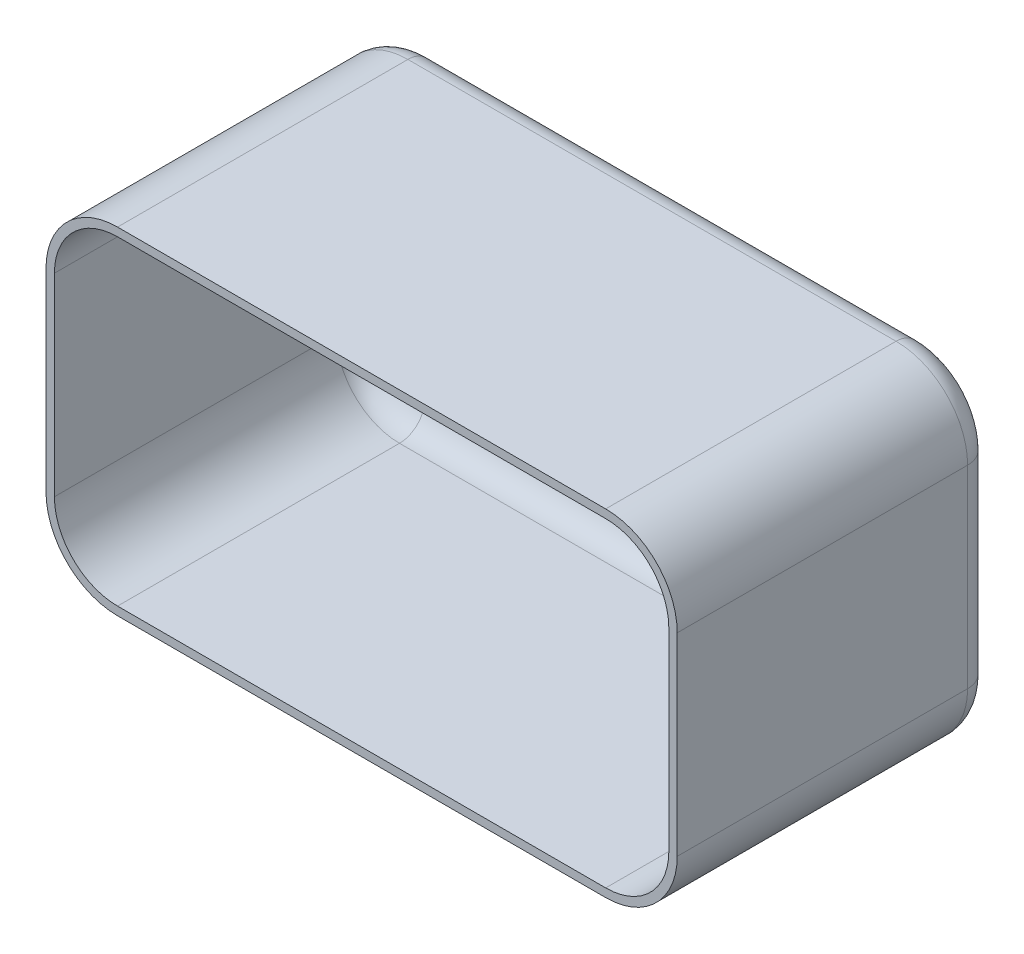
SolidWorks part; units mm, degrees
ref_plane "Front Plane" through (0, 0, 0) normal (0, 0, 1) x (1, 0, 0)
ref_plane "Top Plane" through (0, 0, 0) normal (0, 1, 0) x (1, 0, 0)
ref_plane "Right Plane" through (0, 0, 0) normal (1, 0, 0) x (0, 0, -1)
sketch "Sketch2" plane through (0, 0, 0) normal (0, 0, 1) x (1, 0, 0)
  line L0 (-109.9765, 34.4455) -> (-109.9765, 160.845) construction
  line L1 (-167.9765, 146.2573) -> (-51.9765, 146.2573)
  line L2 (-184.9765, 129.2573) -> (-184.9765, 83.2573)
  line L3 (-167.9765, 66.2573) -> (-51.9765, 66.2573)
  line L4 (-34.9765, 129.2573) -> (-34.9765, 83.2573)
  line L5 (-167.9765, 144.2573) -> (-51.9765, 144.2573)
  line L6 (-36.9765, 129.2573) -> (-36.9765, 83.2573)
  line L7 (-167.9765, 68.2573) -> (-51.9765, 68.2573)
  line L8 (-182.9765, 129.2573) -> (-182.9765, 83.2573)
  arc A1 (-51.9765, 146.2573) -> (-34.9765, 129.2573) centre (-51.9765, 129.2573) cw
  arc A2 (-51.9765, 66.2573) -> (-34.9765, 83.2573) centre (-51.9765, 83.2573) ccw
  arc A3 (-184.9765, 83.2573) -> (-167.9765, 66.2573) centre (-167.9765, 83.2573) ccw
  arc A4 (-167.9765, 146.2573) -> (-184.9765, 129.2573) centre (-167.9765, 129.2573) ccw
  arc A5 (-51.9765, 144.2573) -> (-36.9765, 129.2573) centre (-51.9765, 129.2573) cw
  arc A6 (-51.9765, 68.2573) -> (-36.9765, 83.2573) centre (-51.9765, 83.2573) ccw
  arc A7 (-182.9765, 83.2573) -> (-167.9765, 68.2573) centre (-167.9765, 83.2573) ccw
  arc A8 (-167.9765, 144.2573) -> (-182.9765, 129.2573) centre (-167.9765, 129.2573) ccw
  point P12 (-34.9765, 146.2573)
  point P17 (-184.9765, 66.2573)
  point P20 (-184.9765, 146.2573)
  dimension "D4" = 17
  dimension "D1" = 75
  dimension "D2" = 150
  dimension "D3" = 80
  dimension "D6" = 2
extrude "Boss-Extrude1" add sketch "Sketch2" along normal blind 75
sketch "Sketch3" plane through (0, 0, 0) normal (0, 0, -1) x (-1, 0, 0)
  line L4 (34.9765, 129.2573) -> (34.9765, 83.2573)
  line L5 (51.9765, 66.2573) -> (167.9765, 66.2573)
  line L6 (184.9765, 83.2573) -> (184.9765, 129.2573)
  line L7 (167.9765, 146.2573) -> (51.9765, 146.2573)
  line L8 (34.9765, 129.2573) -> (34.9765, 83.2573)
  line L9 (51.9765, 66.2573) -> (167.9765, 66.2573)
  line L10 (184.9765, 83.2573) -> (184.9765, 129.2573)
  line L11 (167.9765, 146.2573) -> (51.9765, 146.2573)
  arc A4 (51.9765, 146.2573) -> (34.9765, 129.2573) centre (51.9765, 129.2573) ccw
  arc A5 (34.9765, 83.2573) -> (51.9765, 66.2573) centre (51.9765, 83.2573) ccw
  arc A6 (167.9765, 66.2573) -> (184.9765, 83.2573) centre (167.9765, 83.2573) ccw
  arc A7 (184.9765, 129.2573) -> (167.9765, 146.2573) centre (167.9765, 129.2573) ccw
  arc A8 (51.9765, 146.2573) -> (34.9765, 129.2573) centre (51.9765, 129.2573) ccw
  arc A9 (34.9765, 83.2573) -> (51.9765, 66.2573) centre (51.9765, 83.2573) ccw
  arc A10 (167.9765, 66.2573) -> (184.9765, 83.2573) centre (167.9765, 83.2573) ccw
  arc A11 (184.9765, 129.2573) -> (167.9765, 146.2573) centre (167.9765, 129.2573) ccw
  dimension "D1" = 0
extrude "Boss-Extrude2" add sketch "Sketch3" against normal blind 2
fillet "Fillet1" radius 6 16 edges at (-39.9556, 71.2365, 0) (-109.9765, 66.2573, 0) (-179.9973, 71.2365, 0) (-184.9765, 106.2573, 0) (-179.9973, 141.2781, 0) (-109.9765, 146.2573, 0) (-39.9556, 141.2781, 0) (-41.3699, 139.8639, 2) (-109.9765, 144.2573, 2) (-178.5831, 139.8639, 2) (-182.9765, 106.2573, 2) (-178.5831, 72.6507, 2) (-109.9765, 68.2573, 2) (-41.3699, 72.6507, 2) (-34.9765, 106.2573, 0) (-36.9765, 106.2573, 2)
